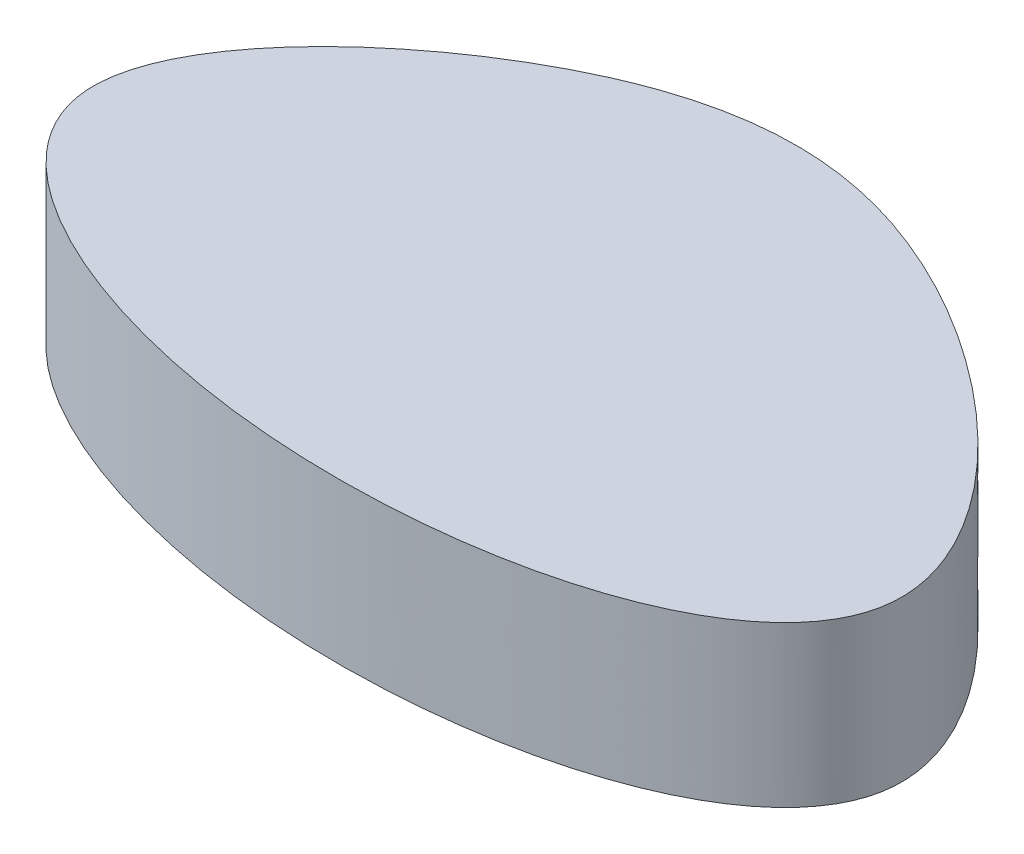
SolidWorks part; units mm, degrees
ref_plane "Front Plane" through (0, 0, 0) normal (0, 0, 1) x (1, 0, 0)
ref_plane "Top Plane" through (0, 0, 0) normal (0, 1, 0) x (1, 0, 0)
ref_plane "Right Plane" through (0, 0, 0) normal (1, 0, 0) x (0, 0, -1)
sketch "Sketch1" plane through (0, 0, 0) normal (0, 1, 0) x (1, 0, 0)
  spline S0 degree 3 poles (-167.7528, -31.6837) (-63.6175, 62.2673) (38.6571, 71.1443) (186.1924, -60.859) (-20.3818, -107.9452) (-167.7528, -31.6837) (-63.6175, 62.2673) (38.6571, 71.1443) knots -0.639677 -0.363081 -0.182563 0 0.126641 0.360323 0.636919 0.817437 1 1.126641 1.360323 1.636919 only from (-54.3402, 54.0791) to (-54.3402, 54.0791)
extrude "Boss-Extrude1" add sketch "Sketch1" along normal blind 46.736
sketch "Sketch2" plane through (0, 46.736, 0) normal (0, 1, 0) x (1, 0, 0)
  spline S2 degree 3 poles (-36.3503, -67.8831) (-29.5308, -69.0807) (-24.0745, -69.8311) (-13.1603, -70.9619) (-7.7026, -71.3421) (3.2143, -71.7499) (8.6735, -71.7774) (19.5931, -71.4739) (25.0536, -71.1432) (35.976, -70.0892) (41.4393, -69.3668) (52.3625, -67.4522) (57.7556, -66.2729) (65.7152, -64.0841) (68.3466, -63.2838) (73.5572, -61.5145) (76.1365, -60.5459) (79.9559, -58.9324) (81.2207, -58.3677) (83.7309, -57.1754) (84.9792, -56.5462) (88.6546, -54.5648) (91.021, -53.1196) (94.3843, -50.6759) (95.474, -49.8149) (97.0461, -48.4307) (97.5609, -47.9524) (98.5565, -46.968) (99.0377, -46.4615) (99.9612, -45.4156) (100.4037, -44.8761) (101.242, -43.7572) (101.6396, -43.1749) (102.7302, -41.3791) (103.3219, -40.1204) (103.8259, -38.44) (103.915, -38.0972) (104.0655, -37.4118) (104.1273, -37.0683) (104.2732, -36.0351) (104.3167, -35.3428) (104.3151, -33.9525) (104.2706, -33.2519) (104.113, -31.858) (104.0009, -31.17) (103.5868, -29.1268) (103.2081, -27.7922) (102.3081, -25.1613) (101.7835, -23.8605) (100.6388, -21.3249) (100.0179, -20.0867) (98.7001, -17.6567) (98.0029, -16.4649) (95.8168, -12.9474) (94.2341, -10.6788) (91.7171, -7.3629) (90.8531, -6.2714) (89.0938, -4.1295) (88.1971, -3.0773) (85.461, 0.0294) (83.5761, 2.034) (77.7667, 7.8786) (73.6897, 11.5519) (67.3177, 16.7813) (65.1503, 18.4771) (61.8358, 20.9513) (60.7204, 21.7645) (58.4683, 23.3676) (57.3304, 24.1584) (51.6078, 28.0401) (46.922, 30.9196) (37.3237, 36.203) (32.4119, 38.6083) (24.8361, 41.78) (22.2758, 42.7637) (17.0717, 44.5559) (14.4274, 45.3636) (11.0576, 46.2378) (10.38, 46.406) (9.0251, 46.7267) (8.3471, 46.8793) (6.3113, 47.3139) (4.9517, 47.5723) (0.8655, 48.2503) (-1.8684, 48.5722) (-7.3574, 48.9394) (-10.1123, 48.9846) (-14.2612, 48.8368) (-15.6468, 48.7516) (-17.7294, 48.5695) (-18.4253, 48.4997) (-19.8121, 48.3426) (-26.0311, 47.5577) (-32.0643, 46.0892) (-39.936, 43.4956) (-42.5311, 42.5251) (-46.3861, 40.9305) (-47.6653, 40.3754) (-50.1952, 39.23) (-51.4481, 38.6387) (-55.1736, 36.8139) (-57.6131, 35.5294) (-62.4133, 32.839) (-64.7738, 31.433) (-71.7427, 27.0416) (-76.2403, 23.8857) (-82.7513, 18.7896) (-84.8819, 17.0298) (-88.0114, 14.2879) (-89.0447, 13.3556) (-91.081, 11.4598) (-92.0827, 10.4977) (-95.0348, 7.5655) (-96.9329, 5.55) (-100.5593, 1.3721) (-102.2884, -0.7898) (-104.7125, -4.1793) (-105.4931, -5.3354) (-106.9799, -7.701) (-107.6831, -8.9052) (-108.9901, -11.3663) (-109.5943, -12.623) (-110.6719, -15.2058) (-111.1392, -16.5168) (-111.878, -19.185) (-112.152, -20.5427) (-112.3368, -22.6349) (-112.3591, -23.3442) (-112.3045, -24.7383) (-112.2269, -25.4281) (-111.9745, -26.7935) (-111.8, -27.4693) (-111.3631, -28.8079) (-111.1039, -29.4608) (-110.2343, -31.3609) (-109.5303, -32.5597) (-108.3433, -34.2863) (-107.9241, -34.8512) (-107.0568, -35.9475) (-106.6081, -36.48) (-105.2238, -38.0379) (-104.2504, -39.0238) (-102.2259, -40.9149) (-101.1746, -41.8199) (-99.0083, -43.5635) (-97.8902, -44.404) (-94.4869, -46.8188) (-92.1474, -48.2933) (-87.3657, -51.046) (-84.9231, -52.3232) (-79.9552, -54.7193) (-77.4298, -55.8378) (-72.3084, -57.94) (-69.7083, -58.9246) (-61.8657, -61.6809) (-56.5688, -63.2632) (-48.5382, -65.3194) (-45.847, -65.9513) (-41.7896, -66.8226) (-40.4337, -67.1002) (-37.7151, -67.6303) (-36.3503, -67.8831) (-29.5308, -69.0807) (-24.0745, -69.8311) knots -0.007812 -0.007812 0 0 0.03125 0.03125 0.0625 0.0625 0.09375 0.09375 0.125 0.125 0.15625 0.15625 0.1875 0.1875 0.203125 0.203125 0.21875 0.21875 0.226563 0.226563 0.234375 0.234375 0.25 0.25 0.257813 0.257813 0.261719 0.261719 0.265625 0.265625 0.269531 0.269531 0.273438 0.273438 0.28125 0.28125 0.283203 0.283203 0.285156 0.285156 0.289063 0.289063 0.292969 0.292969 0.296875 0.296875 0.304688 0.304688 0.3125 0.3125 0.320313 0.320313 0.328125 0.328125 0.34375 0.34375 0.351563 0.351563 0.359375 0.359375 0.375 0.375 0.40625 0.40625 0.421875 0.421875 0.429688 0.429688 0.4375 0.4375 0.46875 0.46875 0.5 0.5 0.515625 0.515625 0.53125 0.53125 0.535156 0.535156 0.539063 0.539063 0.546875 0.546875 0.5625 0.5625 0.578125 0.578125 0.585938 0.585938 0.589844 0.589844 0.59375 0.625 0.625 0.640625 0.640625 0.648438 0.648438 0.65625 0.65625 0.671875 0.671875 0.6875 0.6875 0.71875 0.71875 0.734375 0.734375 0.742188 0.742188 0.75 0.75 0.765625 0.765625 0.78125 0.78125 0.789063 0.789063 0.796875 0.796875 0.804688 0.804688 0.8125 0.8125 0.820313 0.820313 0.824219 0.824219 0.828125 0.828125 0.832031 0.832031 0.835938 0.835938 0.84375 0.84375 0.847656 0.847656 0.851563 0.851563 0.859375 0.859375 0.867188 0.867188 0.875 0.875 0.890625 0.890625 0.90625 0.90625 0.921875 0.921875 0.9375 0.9375 0.96875 0.96875 0.984375 0.984375 0.992188 0.992188 1 1 1.03125 1.03125 1.0625 only from (-34.9864, -68.1226) to (-34.9864, -68.1226)
  spline S3 degree 3 poles (-36.3503, -67.8831) (-29.5308, -69.0807) (-24.0745, -69.8311) (-13.1603, -70.9619) (-7.7026, -71.3421) (3.2143, -71.7499) (8.6735, -71.7774) (19.5931, -71.4739) (25.0536, -71.1432) (35.976, -70.0892) (41.4393, -69.3668) (52.3625, -67.4522) (57.7556, -66.2729) (65.7152, -64.0841) (68.3466, -63.2838) (73.5572, -61.5145) (76.1365, -60.5459) (79.9559, -58.9324) (81.2207, -58.3677) (83.7309, -57.1754) (84.9792, -56.5462) (88.6546, -54.5648) (91.021, -53.1196) (94.3843, -50.6759) (95.474, -49.8149) (97.0461, -48.4307) (97.5609, -47.9524) (98.5565, -46.968) (99.0377, -46.4615) (99.9612, -45.4156) (100.4037, -44.8761) (101.242, -43.7572) (101.6396, -43.1749) (102.7302, -41.3791) (103.3219, -40.1204) (103.8259, -38.44) (103.915, -38.0972) (104.0655, -37.4118) (104.1273, -37.0683) (104.2732, -36.0351) (104.3167, -35.3428) (104.3151, -33.9525) (104.2706, -33.2519) (104.113, -31.858) (104.0009, -31.17) (103.5868, -29.1268) (103.2081, -27.7922) (102.3081, -25.1613) (101.7835, -23.8605) (100.6388, -21.3249) (100.0179, -20.0867) (98.7001, -17.6567) (98.0029, -16.4649) (95.8168, -12.9474) (94.2341, -10.6788) (91.7171, -7.3629) (90.8531, -6.2714) (89.0938, -4.1295) (88.1971, -3.0773) (85.461, 0.0294) (83.5761, 2.034) (77.7667, 7.8786) (73.6897, 11.5519) (67.3177, 16.7813) (65.1503, 18.4771) (61.8358, 20.9513) (60.7204, 21.7645) (58.4683, 23.3676) (57.3304, 24.1584) (51.6078, 28.0401) (46.922, 30.9196) (37.3237, 36.203) (32.4119, 38.6083) (24.8361, 41.78) (22.2758, 42.7637) (17.0717, 44.5559) (14.4274, 45.3636) (11.0576, 46.2378) (10.38, 46.406) (9.0251, 46.7267) (8.3471, 46.8793) (6.3113, 47.3139) (4.9517, 47.5723) (0.8655, 48.2503) (-1.8684, 48.5722) (-7.3574, 48.9394) (-10.1123, 48.9846) (-14.2612, 48.8368) (-15.6468, 48.7516) (-17.7294, 48.5695) (-18.4253, 48.4997) (-19.8121, 48.3426) (-26.0311, 47.5577) (-32.0643, 46.0892) (-39.936, 43.4956) (-42.5311, 42.5251) (-46.3861, 40.9305) (-47.6653, 40.3754) (-50.1952, 39.23) (-51.4481, 38.6387) (-55.1736, 36.8139) (-57.6131, 35.5294) (-62.4133, 32.839) (-64.7738, 31.433) (-71.7427, 27.0416) (-76.2403, 23.8857) (-82.7513, 18.7896) (-84.8819, 17.0298) (-88.0114, 14.2879) (-89.0447, 13.3556) (-91.081, 11.4598) (-92.0827, 10.4977) (-95.0348, 7.5655) (-96.9329, 5.55) (-100.5593, 1.3721) (-102.2884, -0.7898) (-104.7125, -4.1793) (-105.4931, -5.3354) (-106.9799, -7.701) (-107.6831, -8.9052) (-108.9901, -11.3663) (-109.5943, -12.623) (-110.6719, -15.2058) (-111.1392, -16.5168) (-111.878, -19.185) (-112.152, -20.5427) (-112.3368, -22.6349) (-112.3591, -23.3442) (-112.3045, -24.7383) (-112.2269, -25.4281) (-111.9745, -26.7935) (-111.8, -27.4693) (-111.3631, -28.8079) (-111.1039, -29.4608) (-110.2343, -31.3609) (-109.5303, -32.5597) (-108.3433, -34.2863) (-107.9241, -34.8512) (-107.0568, -35.9475) (-106.6081, -36.48) (-105.2238, -38.0379) (-104.2504, -39.0238) (-102.2259, -40.9149) (-101.1746, -41.8199) (-99.0083, -43.5635) (-97.8902, -44.404) (-94.4869, -46.8188) (-92.1474, -48.2933) (-87.3657, -51.046) (-84.9231, -52.3232) (-79.9552, -54.7193) (-77.4298, -55.8378) (-72.3084, -57.94) (-69.7083, -58.9246) (-61.8657, -61.6809) (-56.5688, -63.2632) (-48.5382, -65.3194) (-45.847, -65.9513) (-41.7896, -66.8226) (-40.4337, -67.1002) (-37.7151, -67.6303) (-36.3503, -67.8831) (-29.5308, -69.0807) (-24.0745, -69.8311) knots -0.007812 -0.007812 0 0 0.03125 0.03125 0.0625 0.0625 0.09375 0.09375 0.125 0.125 0.15625 0.15625 0.1875 0.1875 0.203125 0.203125 0.21875 0.21875 0.226563 0.226563 0.234375 0.234375 0.25 0.25 0.257813 0.257813 0.261719 0.261719 0.265625 0.265625 0.269531 0.269531 0.273438 0.273438 0.28125 0.28125 0.283203 0.283203 0.285156 0.285156 0.289063 0.289063 0.292969 0.292969 0.296875 0.296875 0.304688 0.304688 0.3125 0.3125 0.320313 0.320313 0.328125 0.328125 0.34375 0.34375 0.351563 0.351563 0.359375 0.359375 0.375 0.375 0.40625 0.40625 0.421875 0.421875 0.429688 0.429688 0.4375 0.4375 0.46875 0.46875 0.5 0.5 0.515625 0.515625 0.53125 0.53125 0.535156 0.535156 0.539063 0.539063 0.546875 0.546875 0.5625 0.5625 0.578125 0.578125 0.585938 0.585938 0.589844 0.589844 0.59375 0.625 0.625 0.640625 0.640625 0.648438 0.648438 0.65625 0.65625 0.671875 0.671875 0.6875 0.6875 0.71875 0.71875 0.734375 0.734375 0.742188 0.742188 0.75 0.75 0.765625 0.765625 0.78125 0.78125 0.789063 0.789063 0.796875 0.796875 0.804688 0.804688 0.8125 0.8125 0.820313 0.820313 0.824219 0.824219 0.828125 0.828125 0.832031 0.832031 0.835938 0.835938 0.84375 0.84375 0.847656 0.847656 0.851563 0.851563 0.859375 0.859375 0.867188 0.867188 0.875 0.875 0.890625 0.890625 0.90625 0.90625 0.921875 0.921875 0.9375 0.9375 0.96875 0.96875 0.984375 0.984375 0.992188 0.992188 1 1 1.03125 1.03125 1.0625 only from (-34.9864, -68.1226) to (-34.9864, -68.1226)
  dimension "D1" = 15.24
